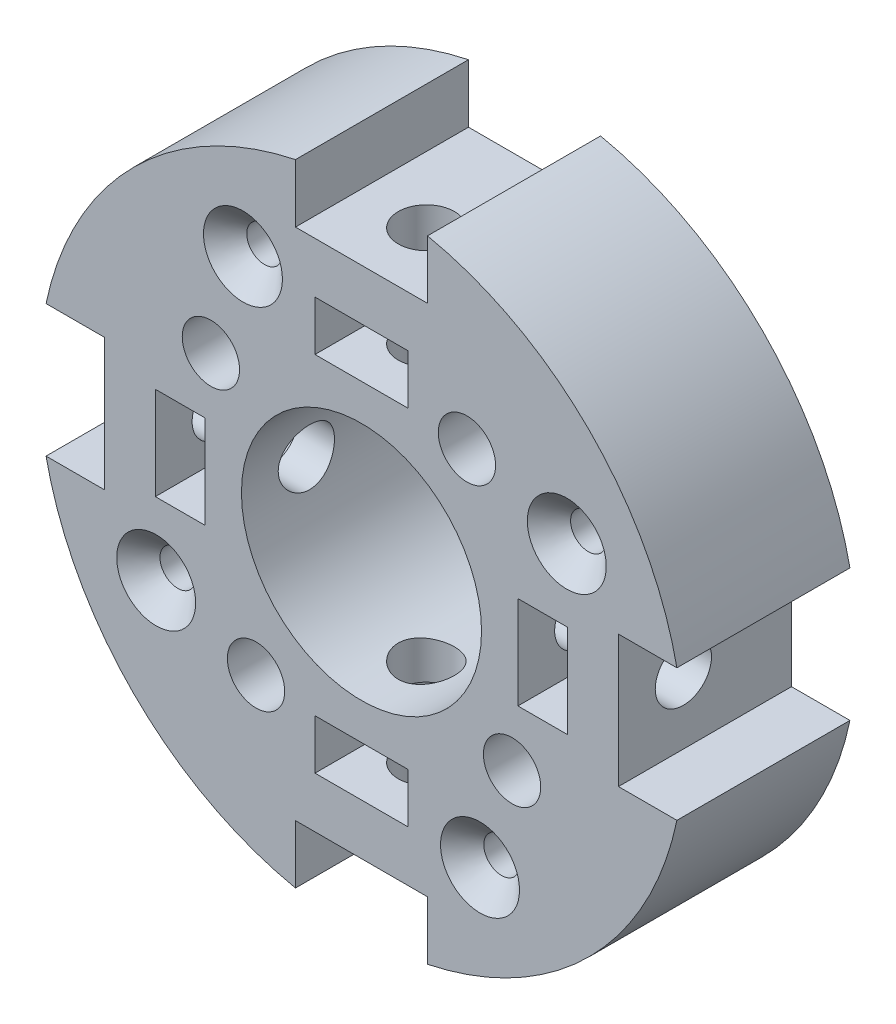
SolidWorks part; units mm, degrees
ref_plane "Plan de face" through (0, 0, 0) normal (0, 0, 1) x (1, 0, 0)
ref_plane "Plan de dessus" through (0, 0, 0) normal (0, 1, 0) x (1, 0, 0)
ref_plane "Plan de droite" through (0, 0, 0) normal (1, 0, 0) x (0, 0, -1)
sketch "Esquisse1" plane through (0, 0, 0) normal (0, 0, 1) x (1, 0, 0)
  line L1 (-29.4129, -5.9059) -> (-23.9629, -5.9059) construction
  line L3 (-29.4129, 5.9059) -> (-23.9629, 5.9059) construction
  line L4 (-23.9629, -5.9059) -> (-23.9629, 5.9059) construction
  line L5 (-29.4129, -5.9059) -> (-23.9629, 5.9059) construction
  line L6 (-29.4129, 5.9059) -> (-23.9629, -5.9059) construction
  line L7 (-5.9059, 29.4129) -> (-5.9059, 23.9629) construction
  line L8 (-5.9059, 23.9629) -> (5.9059, 23.9629) construction
  line L9 (5.9059, 29.4129) -> (5.9059, 23.9629) construction
  line L11 (29.4129, 5.9059) -> (23.9629, 5.9059) construction
  line L12 (23.9629, 5.9059) -> (23.9629, -5.9059) construction
  line L13 (29.4129, -5.9059) -> (23.9629, -5.9059) construction
  line L15 (5.9059, -29.4129) -> (5.9059, -23.9629) construction
  line L16 (5.9059, -23.9629) -> (-5.9059, -23.9629) construction
  line L17 (-5.9059, -29.4129) -> (-5.9059, -23.9629) construction
  line L18 (-6.1059, 29.1677) -> (-6.1059, 23.7629)
  line L19 (-6.1059, 23.7629) -> (6.1059, 23.7629)
  line L20 (6.1059, 29.1677) -> (6.1059, 23.7629)
  line L21 (29.1677, 6.1059) -> (23.7629, 6.1059)
  line L22 (23.7629, 6.1059) -> (23.7629, -6.1059)
  line L23 (29.1677, -6.1059) -> (23.7629, -6.1059)
  line L24 (6.1059, -29.1677) -> (6.1059, -23.7629)
  line L25 (6.1059, -23.7629) -> (-6.1059, -23.7629)
  line L26 (-6.1059, -29.1677) -> (-6.1059, -23.7629)
  line L27 (-29.1677, -6.1059) -> (-23.7629, -6.1059)
  line L28 (-23.7629, -6.1059) -> (-23.7629, 6.1059)
  line L29 (-29.1677, 6.1059) -> (-23.7629, 6.1059)
  line L30 (-4.3, 19.0629) -> (4.3, 19.0629)
  line L31 (-4, 18.7629) -> (4, 18.7629) construction
  line L32 (-4, 18.7629) -> (-4, 14.7629) construction
  line L33 (-4, 14.7629) -> (4, 14.7629) construction
  line L34 (4, 18.7629) -> (4, 14.7629) construction
  line L35 (-4, 18.7629) -> (4, 14.7629) construction
  line L36 (-4, 14.7629) -> (4, 18.7629) construction
  line L37 (4.3, 19.0629) -> (4.3, 14.4629)
  line L38 (-4.3, 14.4629) -> (4.3, 14.4629)
  line L39 (-4.3, 19.0629) -> (-4.3, 14.4629)
  line L40 (19.0629, 4.3) -> (19.0629, -4.3)
  line L41 (19.0629, -4.3) -> (14.4629, -4.3)
  line L42 (14.4629, 4.3) -> (14.4629, -4.3)
  line L43 (19.0629, 4.3) -> (14.4629, 4.3)
  line L44 (4.3, -19.0629) -> (-4.3, -19.0629)
  line L45 (-4.3, -19.0629) -> (-4.3, -14.4629)
  line L46 (4.3, -14.4629) -> (-4.3, -14.4629)
  line L47 (4.3, -19.0629) -> (4.3, -14.4629)
  line L48 (-19.0629, -4.3) -> (-19.0629, 4.3)
  line L49 (-19.0629, 4.3) -> (-14.4629, 4.3)
  line L50 (-14.4629, -4.3) -> (-14.4629, 4.3)
  line L51 (-19.0629, -4.3) -> (-14.4629, -4.3)
  line L52 (-0.2119, 0.3671) -> (-25000.2119, 43301.6373) construction
  line L53 (0, 0) -> (-40957.6022, 28678.8218) construction
  line L54 (0, -1000) -> (0, 49000) construction
  arc A0 (-29.4129, -5.9059) -> (-5.9059, -29.4129) centre (0, 0) ccw construction
  circle A1 centre (0, 0) radius 11.1
  circle A2 centre (-10.9602, 18.9835) radius 1.65
  circle A3 centre (18.9835, 10.9602) radius 1.65
  circle A4 centre (10.9602, -18.9835) radius 1.65
  circle A5 centre (-18.9835, -10.9602) radius 1.65
  arc A6 (5.9059, -29.4129) -> (29.4129, -5.9059) centre (0, 0) ccw construction
  arc A7 (29.4129, 5.9059) -> (5.9059, 29.4129) centre (0, 0) ccw construction
  arc A8 (-5.9059, 29.4129) -> (-29.4129, 5.9059) centre (0, 0) ccw construction
  arc A9 (29.1677, 6.1059) -> (6.1059, 29.1677) centre (0, 0) ccw
  arc A10 (6.1059, -29.1677) -> (29.1677, -6.1059) centre (0, 0) ccw
  arc A11 (-29.1677, -6.1059) -> (-6.1059, -29.1677) centre (0, 0) ccw
  arc A12 (-6.1059, 29.1677) -> (-29.1677, 6.1059) centre (0, 0) ccw
  circle A13 centre (-13.9256, 9.7508) radius 2.65
  circle A14 centre (9.7508, 13.9256) radius 2.65
  circle A15 centre (13.9256, -9.7508) radius 2.65
  circle A16 centre (-9.7508, -13.9256) radius 2.65
  point P4 (-26.6879, 0)
  point P22 (0, 0)
  point P33 (0, 0)
  point P51 (0, 16.7629)
  point P56 (0, 23.7629)
  point P75 (0, 0)
  point P90 (0, 0)
  dimension "D1" = 60
  dimension "D2" = 22.2
  dimension "D7" = 3.3
  dimension "D14" = 5.3
  dimension "D18" = 4
  dimension "D3" = 5.45
  dimension "D4" = 4
  dimension "D5" = 21.9203
  dimension "D6" = 0.2
  dimension "D9" = 8
  dimension "D10" = 4
  dimension "D11" = 5
  dimension "D15" = 17
  dimension "D16" = 30
  dimension "D17" = 55
  dimension "D12" = 0.3
  dimension "D8" = 4
  dimension "D13" = 4
extrude "Boss.-Extru.1" add sketch "Esquisse1" along normal blind 16
sketch "Esquisse5" plane through (0, 0, 0) normal (0, 0, -1) x (-1, 0, 0)
  line L0 (9.1913, 9.7508) -> (11.5584, 5.6508)
  line L1 (-9.7508, 9.1913) -> (-5.6508, 11.5584)
  line L2 (-5.6508, 11.5584) -> (-5.6508, 16.2927)
  line L3 (-5.6508, 16.2927) -> (-9.7508, 18.6599)
  line L4 (-9.7508, 18.6599) -> (-13.8508, 16.2927)
  line L5 (-13.8508, 16.2927) -> (-13.8508, 11.5584)
  line L6 (-13.8508, 11.5584) -> (-9.7508, 9.1913)
  line L7 (11.5584, 5.6508) -> (16.2927, 5.6508)
  line L8 (16.2927, 5.6508) -> (18.6599, 9.7508)
  line L9 (18.6599, 9.7508) -> (16.2927, 13.8508)
  line L10 (16.2927, 13.8508) -> (11.5584, 13.8508)
  line L11 (11.5584, 13.8508) -> (9.1913, 9.7508)
  line L12 (9.7508, -9.1913) -> (5.6508, -11.5584)
  line L13 (5.6508, -11.5584) -> (5.6508, -16.2927)
  line L14 (5.6508, -16.2927) -> (9.7508, -18.6599)
  line L15 (9.7508, -18.6599) -> (13.8508, -16.2927)
  line L16 (13.8508, -16.2927) -> (13.8508, -11.5584)
  line L17 (13.8508, -11.5584) -> (9.7508, -9.1913)
  line L18 (-9.1913, -9.7508) -> (-11.5584, -5.6508)
  line L19 (-11.5584, -5.6508) -> (-16.2927, -5.6508)
  line L20 (-16.2927, -5.6508) -> (-18.6599, -9.7508)
  line L21 (-18.6599, -9.7508) -> (-16.2927, -13.8508)
  line L22 (-16.2927, -13.8508) -> (-11.5584, -13.8508)
  line L23 (-11.5584, -13.8508) -> (-9.1913, -9.7508)
  circle A0 centre (-9.7508, 13.9256) radius 4.1 construction
  point P30 (0, 0)
  dimension "D1" = 8.2
  dimension "D2" = 4
extrude "Enlèv. mat.-Extru.3" cut sketch "Esquisse5" against normal blind 10
chamfer "Chanfrein1" distance 2 angle 45 4 edges at (-17.3335, -10.9602, 16) (12.6102, -18.9835, 16) (20.6335, 10.9602, 16) (-9.3102, 18.9835, 16)
sketch "Esquisse6" plane through (-23.7629, 0, 0) normal (-1, 0, 0) x (0, 0, 1)
  line L1 (16, -6.1059) -> (16, 6.1059) construction
  circle A0 centre (10, 0) radius 2.6
  dimension "D1" = 5.2
  dimension "D2" = 6
extrude "Enlèv. mat.-Extru.4" cut sketch "Esquisse6" against normal blind 17
pattern_circular "Répétition circulaire1" count 4 every 90 about axis through (0, 0, 0) along (0, 0, 1) of "Enlèv. mat.-Extru.4"
